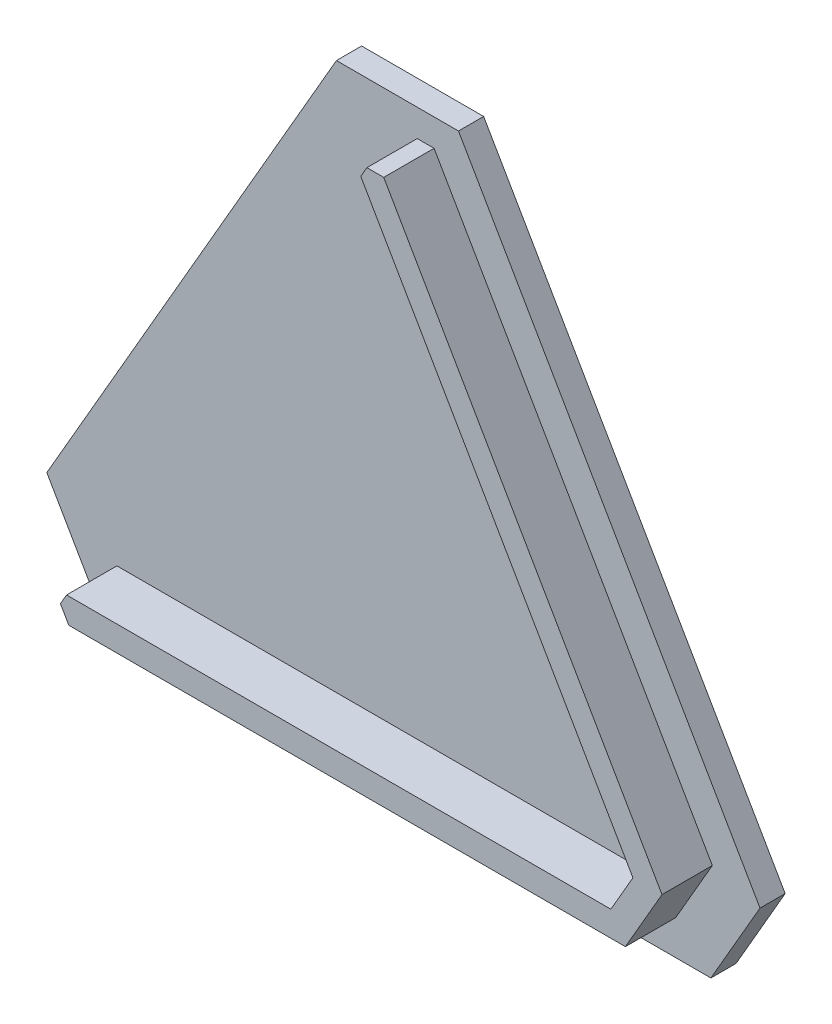
SolidWorks part; units mm, degrees
ref_plane "Front Plane" through (0, 0, 0) normal (0, 0, 1) x (1, 0, 0)
ref_plane "Top Plane" through (0, 0, 0) normal (0, 1, 0) x (1, 0, 0)
ref_plane "Right Plane" through (0, 0, 0) normal (1, 0, 0) x (0, 0, -1)
sketch "Sketch2" plane through (0, 0, 297.1478) normal (0, 0, 1) x (1, 0, 0)
  line L0 (222.116, -44.1065) -> (277.385, -139.8353)
  line L1 (277.385, -139.8353) -> (270.116, -152.4257)
  line L2 (270.116, -152.4257) -> (159.5778, -152.4257)
  line L3 (222.3469, -43.7065) -> (277.8469, -139.8353) construction
  line L4 (277.8469, -139.8353) -> (270.3469, -152.8257) construction
  line L5 (270.3469, -152.8257) -> (159.3469, -152.8257) construction
  line L7 (159.5778, -152.4257) -> (157.9091, -149.5353)
  line L8 (157.9091, -149.5353) -> (159.1271, -147.4257)
  line L9 (159.3469, -152.8257) -> (157.4472, -149.5353) construction
  line L10 (172.6723, -123.1646) -> (157.4472, -149.5353) construction
  line L11 (159.1271, -147.4257) -> (267.2292, -147.4257)
  line L12 (267.2292, -147.4257) -> (271.6115, -139.8353)
  line L13 (271.6115, -139.8353) -> (217.5604, -46.2161)
  line L14 (222.116, -44.1065) -> (218.7784, -44.1065)
  line L15 (218.7784, -44.1065) -> (217.5604, -46.2161)
  line L16 (218.5475, -43.7065) -> (203.3223, -70.0772) construction
  line L17 (218.5475, -43.7065) -> (222.3469, -43.7065) construction
  dimension "D6" = 5
  dimension "D7" = 5
  dimension "D8" = 5
extrude "Boss-Extrude1" add sketch "Sketch2" against normal blind 10
sketch "Sketch3" plane through (0, 0, 297.1478) normal (0, 0, 1) x (1, 0, 0)
  line L0 (202.7281, -38.7065) -> (226.9657, -38.7065)
  line L1 (226.9657, -38.7065) -> (286.8511, -142.431)
  line L2 (286.8511, -142.431) -> (277.0969, -159.3257)
  line L3 (277.0969, -159.3257) -> (157.3262, -159.3257)
  line L4 (157.3262, -159.3257) -> (145.2074, -138.3353)
  line L5 (145.2074, -138.3353) -> (202.7281, -38.7065)
extrude "Boss-Extrude2" add sketch "Sketch3" along normal blind 5
mirror "Mirror1" about plane through (218.7784, -44.1065, 287.1478) normal (0, 0, 1) of bodies 102
delete or keep bodies "Body-Delete1" type delete bodies bodies 102
equation "\"gap\"= 0.4"
